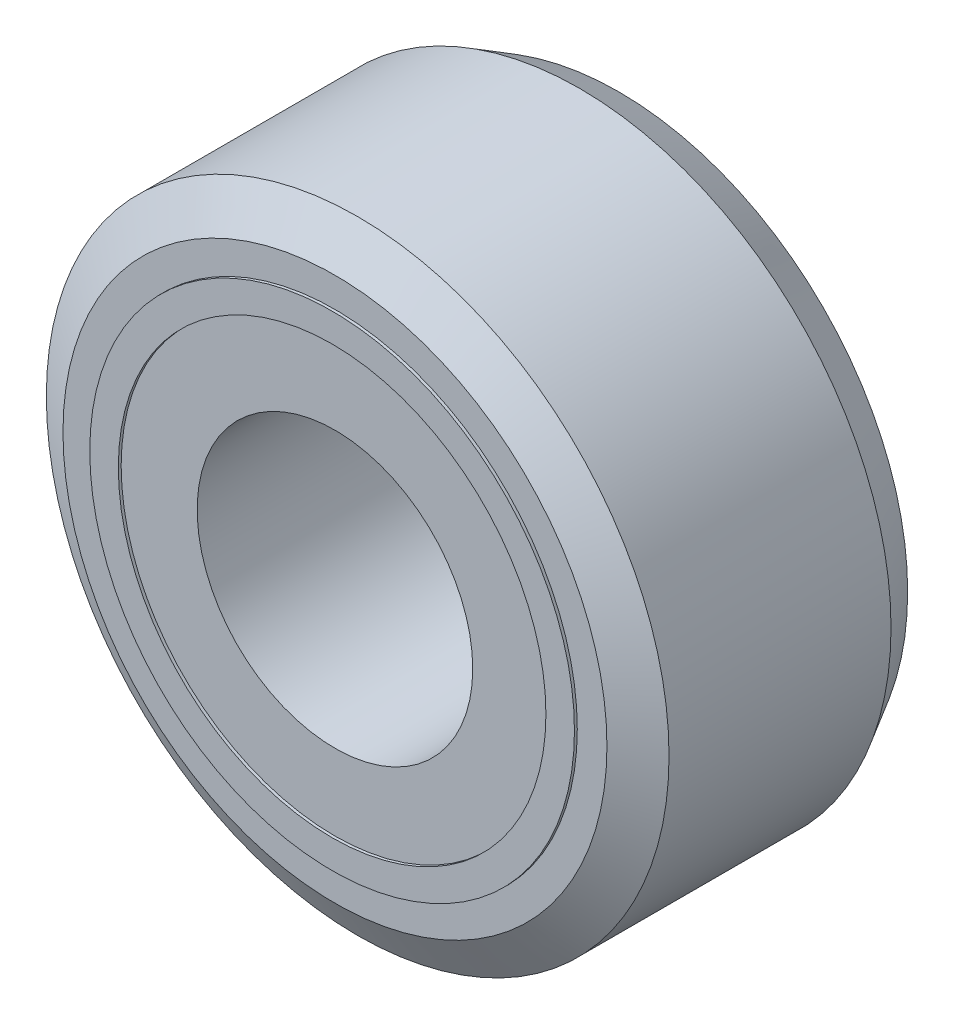
SolidWorks part; units mm, degrees
material "Acero aleado"
ref_plane "Alzado" through (0, 0, 0) normal (0, 0, 1) x (1, 0, 0)
ref_plane "Planta" through (0, 0, 0) normal (0, 1, 0) x (1, 0, 0)
ref_plane "Vista lateral" through (0, 0, 0) normal (1, 0, 0) x (0, 0, -1)
sketch "Croquis1" plane through (0, 0, 0) normal (0, 0, 1) x (1, 0, 0)
  circle A0 centre (0, 0) radius 5.48
  circle A1 centre (0, 0) radius 2.425
  dimension "D1" = 4.85
  dimension "D2" = 10.96
extrude "Saliente-Extruir1" add sketch "Croquis1" along normal mid plane 5
chamfer "Chaflán1" distance 0.4 angle 60 2 edges at (5.48, 0, -2.5) (5.48, 0, 2.5)
sketch "Croquis2" plane through (0, 0, 0) normal (0, 0, -1) x (-1, 0, 0)
  circle A0 centre (0, 0) radius 4.2652
  circle A1 centre (0, 0) radius 3.763
extrude "Saliente-Extruir2" add sketch "Croquis2" along normal mid plane 5.1
